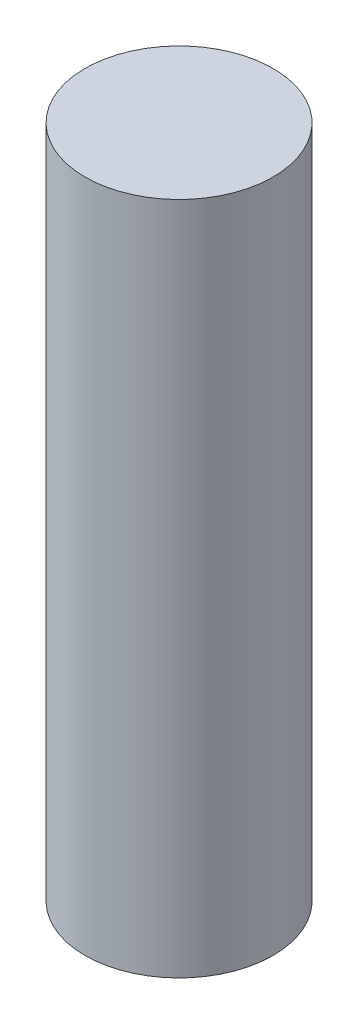
SolidWorks part; units mm, degrees
ref_plane "Front Plane" through (0, 0, 0) normal (0, 0, 1) x (1, 0, 0)
ref_plane "Top Plane" through (0, 0, 0) normal (0, 1, 0) x (1, 0, 0)
ref_plane "Right Plane" through (0, 0, 0) normal (1, 0, 0) x (0, 0, -1)
sketch "Sketch1" plane through (0, 0, 0) normal (0, 1, 0) x (1, 0, 0)
  circle A0 centre (0, 0) radius 7.1755
  dimension "D1" = 14.351
extrude "Boss-Extrude1" add sketch "Sketch1" along normal blind 51.435
